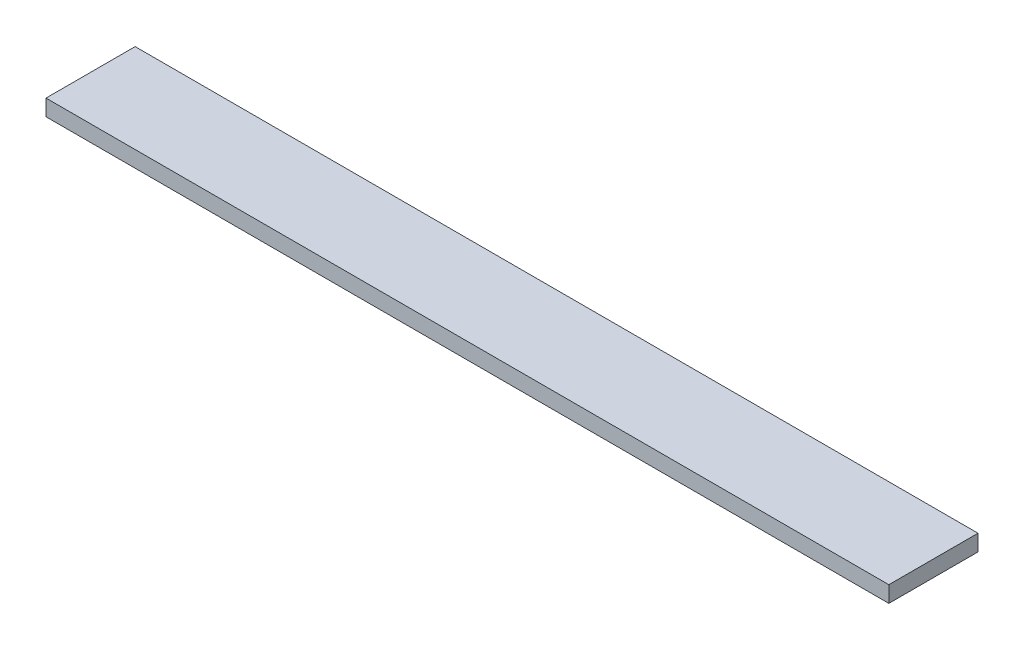
SolidWorks part; units mm, degrees
ref_plane "Front Plane" through (0, 0, 0) normal (0, 0, 1) x (1, 0, 0)
ref_plane "Top Plane" through (0, 0, 0) normal (0, 1, 0) x (1, 0, 0)
ref_plane "Right Plane" through (0, 0, 0) normal (1, 0, 0) x (0, 0, -1)
sketch "Sketch1" plane through (0, 0, 0) normal (0, 1, 0) x (1, 0, 0)
  line L1 (-26, -2.75) -> (26, -2.75)
  line L2 (-26, -2.75) -> (-26, 2.75)
  line L3 (-26, 2.75) -> (26, 2.75)
  line L4 (26, -2.75) -> (26, 2.75)
  line L5 (-26, -2.75) -> (26, 2.75) construction
  line L6 (-26, 2.75) -> (26, -2.75) construction
  point P0 (0, 0)
  dimension "D1" = 52
  dimension "D2" = 5.5
extrude "Boss-Extrude1" add sketch "Sketch1" along normal blind 1
